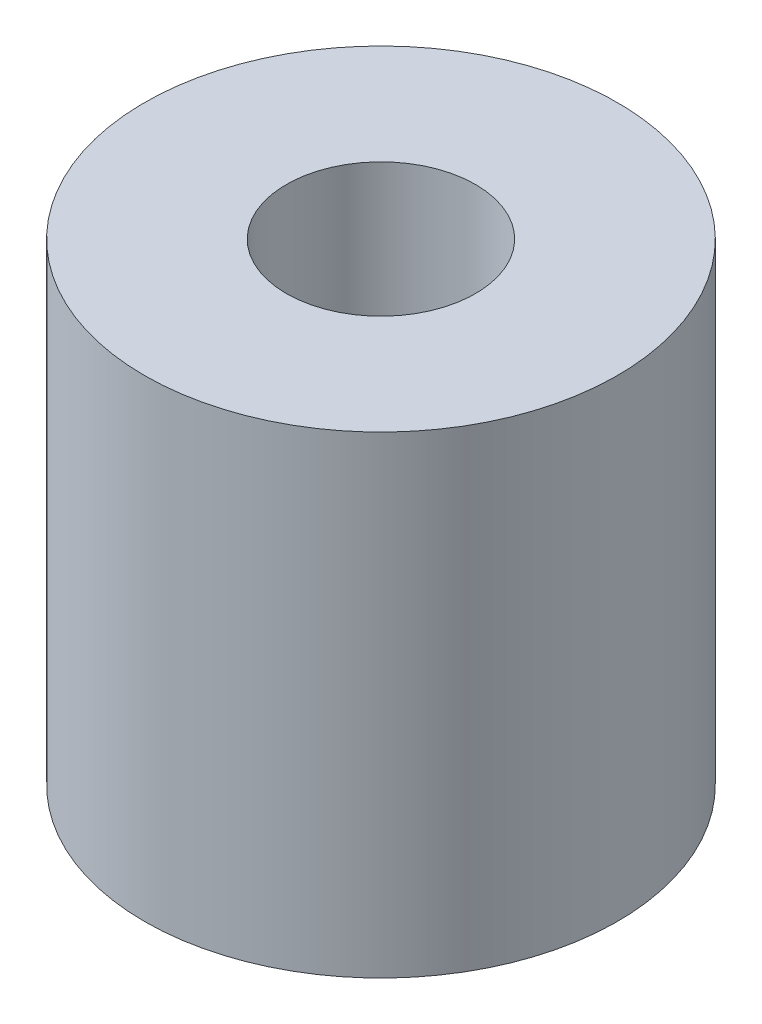
SolidWorks part; units mm, degrees
ref_plane "Front Plane" through (0, 0, 0) normal (0, 0, 1) x (1, 0, 0)
ref_plane "Top Plane" through (0, 0, 0) normal (0, 1, 0) x (1, 0, 0)
ref_plane "Right Plane" through (0, 0, 0) normal (1, 0, 0) x (0, 0, -1)
sketch "Sketch1" plane through (0, 0, 0) normal (0, 1, 0) x (1, 0, 0)
  circle A0 centre (0, 0) radius 25
  circle A1 centre (0, 0) radius 10
  dimension "D1" = 20
  dimension "D2" = 50
extrude "Boss-Extrude1" add sketch "Sketch1" along normal blind 50 contours A0 | A1
